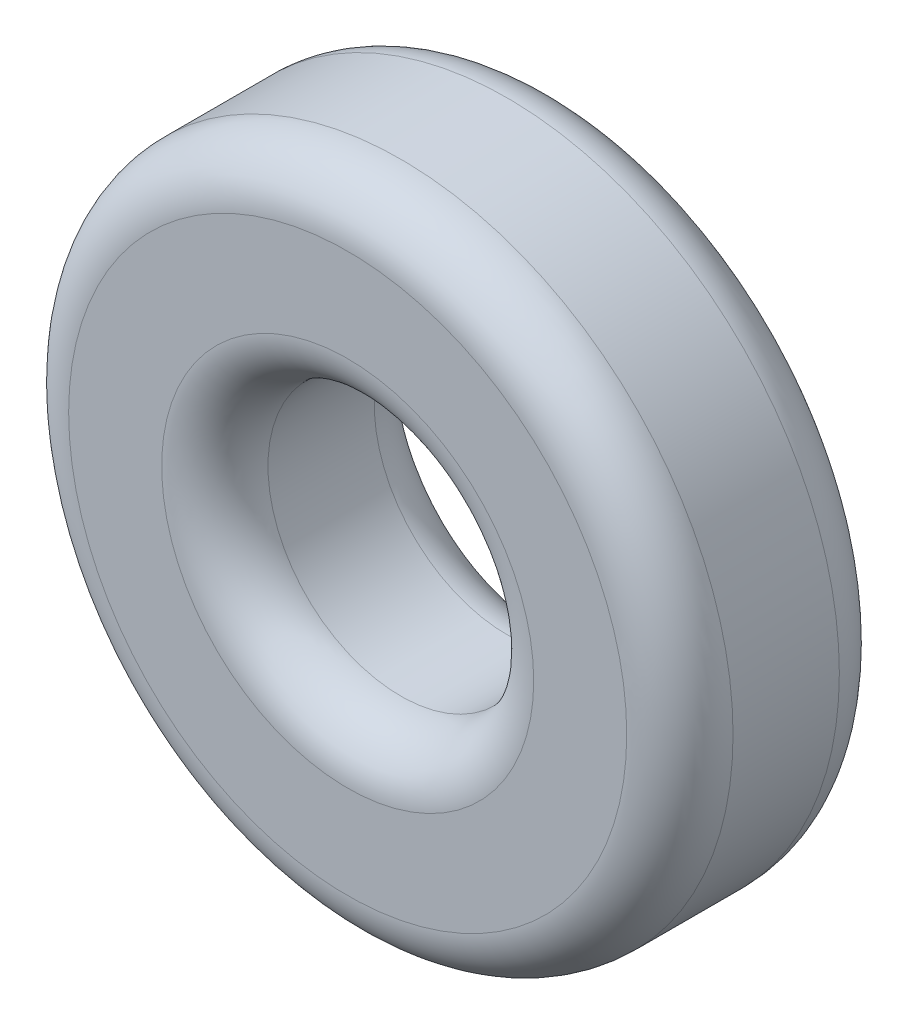
SolidWorks part; units mm, degrees
ref_plane "Спереди" through (0, 0, 0) normal (0, 0, 1) x (1, 0, 0)
ref_plane "Сверху" through (0, 0, 0) normal (0, 1, 0) x (1, 0, 0)
ref_plane "Справа" through (0, 0, 0) normal (1, 0, 0) x (0, 0, -1)
sketch "Эскиз1" plane through (0, 0, 0) normal (0, 0, 1) x (1, 0, 0)
  circle A0 centre (0, 0) radius 12.5
  circle A1 centre (0, 0) radius 5
  dimension "D1" = 25
  dimension "D2" = 10
extrude "Вытянуть1" add sketch "Эскиз1" along normal blind 8
fillet "Скругление1" radius 2 4 edges at (5, 0, 0) (5, 0, 8) (12.5, 0, 0) (12.5, 0, 8)
